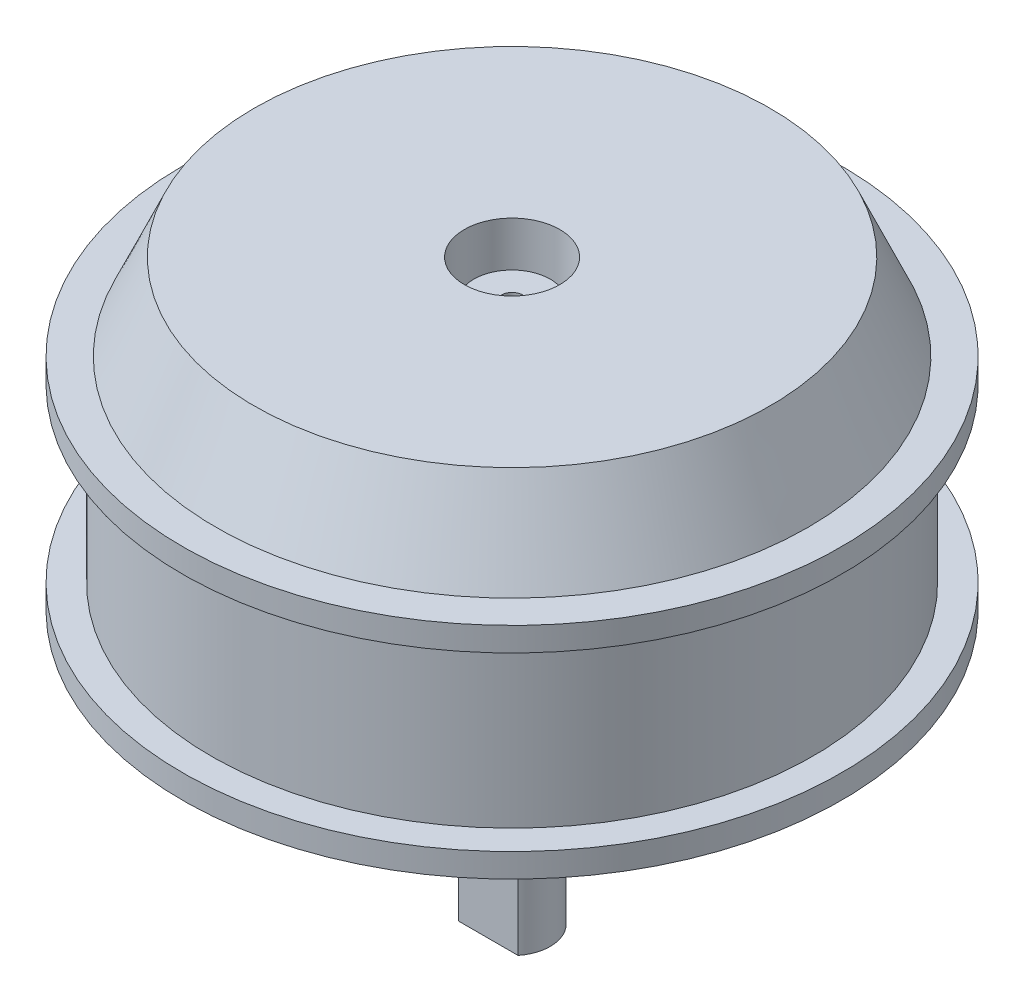
SolidWorks part; units mm, degrees
material "Д16Т ГОСТ 4784-97"
ref_plane "Спереди" through (0, 0, 0) normal (0, 0, 1) x (1, 0, 0)
ref_plane "Сверху" through (0, 0, 0) normal (0, 1, 0) x (1, 0, 0)
ref_plane "Справа" through (0, 0, 0) normal (1, 0, 0) x (0, 0, -1)
other "Configuration Table"
sketch "Эскиз2" plane through (0, 0, 0) normal (0, 0, 1) x (1, 0, 0)
  line L0 (-10, 0) -> (-54, 0)
  line L1 (-54, 0) -> (-62, -18)
  line L2 (-62, -18) -> (-69, -18)
  line L3 (-69, -18) -> (-69, -23)
  line L4 (-69, -23) -> (-63, -23)
  line L5 (-63, -23) -> (-63, -59)
  line L6 (-63, -59) -> (-69, -59)
  line L7 (-69, -59) -> (-69, -64)
  line L8 (-69, -64) -> (-23, -64)
  line L9 (-23, -64) -> (-14, -68)
  line L10 (-14, -68) -> (0, -68)
  line L11 (0, -8) -> (0, -70.5392) construction
  line L12 (0, -8) -> (0, -68)
  line L13 (-8, -11.7306) -> (-8, -8)
  line L14 (0, -8) -> (-8, -8)
  line L15 (-8, -11.7306) -> (-10, -11.7306)
  line L16 (-10, -11.7306) -> (-10, 0)
  dimension "D3" = 7
  dimension "D4" = 18
  dimension "D5" = 5
  dimension "D6" = 36
  dimension "D7" = 5
  dimension "D9" = 4
  dimension "D10" = 6
  dimension "D11" = 6
  dimension "D12" = 8
  dimension "60" = 60
revolve "Повернуть1" add sketch "Эскиз2" angle 360 about L11
sketch "Эскиз3" plane through (0, -68, 0) normal (0, -1, 0) x (1, 0, 0)
  circle A0 centre (0, 0) radius 8
extrude "Бобышка-Вытянуть1" add sketch "Эскиз3" along normal blind 53
sketch "Эскиз4" plane through (0, -121, 0) normal (0, -1, 0) x (1, 0, 0)
  line L1 (-11.0002, 11.8096) -> (10.8692, 11.8096)
  line L2 (-11.0002, 11.8096) -> (-11.0002, 5)
  line L3 (-11.0002, 5) -> (10.8692, 5)
  line L4 (10.8692, 11.8096) -> (10.8692, 5)
  dimension "D1" = 5
extrude "Вырез-Вытянуть1" cut sketch "Эскиз4" against normal blind 46
sketch "Эскиз5" plane through (0, -121, 0) normal (0, -1, 0) x (1, 0, 0)
  circle A0 centre (0, 0) radius 3.5
  dimension "D1" = 7
extrude "Вырез-Вытянуть2" cut sketch "Эскиз5" against normal blind 70
hole_wizard "Зенковка для винта с полупотайной головкой M51" positions "Эскиз6" profile "Эскиз7" countersink size "M5" standard "ISO"
sketch "Эскиз6" plane through (0, -64, 0) normal (0, -1, 0) x (-1, 0, 0)
  point P0 (1.1577, 60)
  dimension "D1" = 60
sketch "Эскиз7" plane through (-1.1577, -64, -60) normal (1, 0, 0) x (0, 0, -1)
  line L0 (0, 0) -> (0, 15.6524)
  line L1 (0, 15.6524) -> (2.75, 14)
  line L2 (2.75, 14) -> (2.75, 2.45)
  line L3 (2.75, 2.45) -> (5.2, 0)
  line L5 (5.2, 0) -> (0, 0)
  line L6 (-2.75, 2.45) -> (-5.2, 0) construction
  line L10 (0, 15.6524) -> (-2.75, 14) construction
  line L11 (0, -6.35) -> (0, 107.95) construction
  dimension "Диаметр отверстия" = 5.5
  dimension "Глубина отверстия" = 14
  dimension "Диаметр передней зенковки" = 10.4
  dimension "Угол передней зенковки" = 90
  dimension "Угол заточки сверла" = 118
pattern_circular "Круговой массив1" count 6 over 360 about axis through (0, 0, 0) along (0, 1, 0) of "Зенковка для винта с полупотайной головкой M51"
sketch "Эскиз8" plane through (0, 0, 0) normal (0, 1, 0) x (1, 0, 0)
  circle A0 centre (0, 0) radius 6
  dimension "D1" = 12
extrude "Вырез-Вытянуть3" [suppressed] cut sketch "Эскиз8" against normal blind 6
sketch "Эскиз9" [suppressed] plane through (0, -6, 0) normal (0, 1, 0) x (1, 0, 0)
  circle A0 centre (0, 0) radius 2.5
  dimension "D1" = 5
extrude "Бобышка-Вытянуть2" [suppressed] add sketch "Эскиз9" along normal blind 12
sketch "Эскиз10" [suppressed] plane through (0, 6, 0) normal (0, 1, 0) x (1, 0, 0)
  circle A0 centre (0, 0) radius 4.5
  dimension "D1" = 9
extrude "Бобышка-Вытянуть3" [suppressed] add sketch "Эскиз10" along normal blind 5
sketch "Эскиз11" [suppressed] plane through (0, 11, 0) normal (0, 1, 0) x (1, 0, 0)
  circle A0 centre (0, 0) radius 2.65
  dimension "D1" = 5.3
extrude "Вырез-Вытянуть4" [suppressed] cut sketch "Эскиз11" against normal blind 3 contours A0
chamfer "Фаска1" [suppressed] distance 1 angle 45
hole_wizard "Отверстие с зазором M41" positions "Эскиз13" profile "Эскиз12" hole size "M4" standard "ISO"
sketch "Эскиз13" plane through (0, -8, 0) normal (0, 1, 0) x (1, 0, 0)
  point P0 (0, 0)
sketch "Эскиз12" plane through (0, -8, 0) normal (1, 0, 0) x (0, 0, 1)
  line L0 (0, 0) -> (0, 15.3519)
  line L1 (0, 15.3519) -> (2.25, 14)
  line L2 (2.25, 14) -> (2.25, 0)
  line L5 (2.25, 0) -> (0, 0)
  line L10 (0, 15.3519) -> (-2.25, 14) construction
  line L11 (0, -6.35) -> (0, 107.95) construction
  dimension "Диаметр отверстия" = 4.5
  dimension "Глубина отверстия" = 14
  dimension "Угол заточки сверла" = 118
sketch "Эскиз14" plane through (0, -68, 0) normal (0, -1, 0) x (1, 0, 0)
  circle A0 centre (0, 0) radius 8
  circle A1 centre (0, 0) radius 9.9506
extrude "Вырез-Вытянуть5" cut sketch "Эскиз14" against normal blind 10
